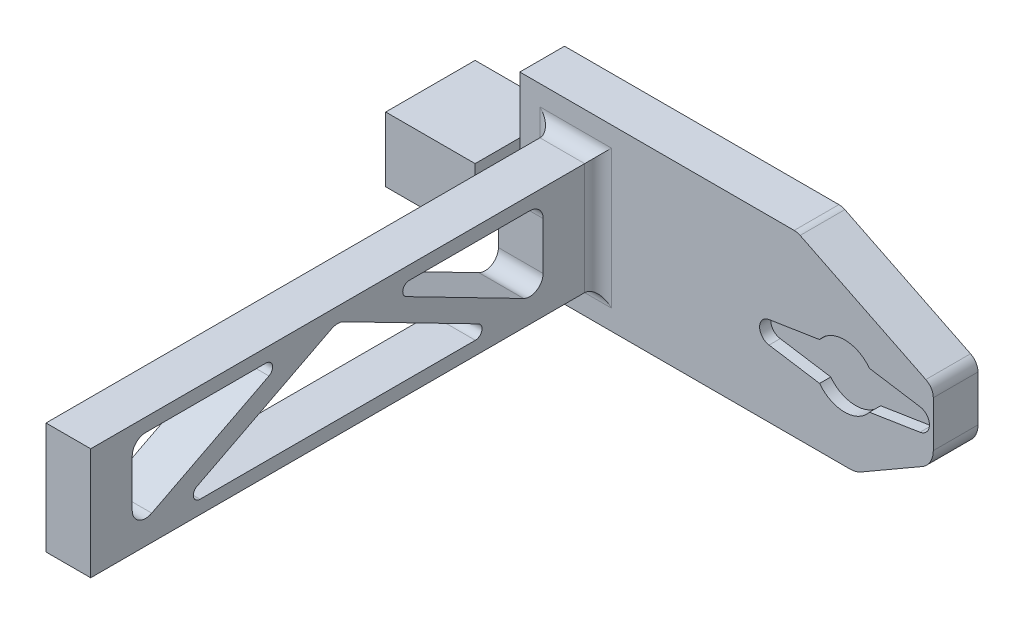
SolidWorks part; units mm, degrees
material "PLA"
ref_plane "Front Plane" through (0, 0, 0) normal (0, 0, 1) x (1, 0, 0)
ref_plane "Top Plane" through (0, 0, 0) normal (0, 1, 0) x (1, 0, 0)
ref_plane "Right Plane" through (0, 0, 0) normal (1, 0, 0) x (0, 0, -1)
sketch "Sketch3" plane through (0, 0, 0) normal (0, 0, 1) x (1, 0, 0)
  line L1 (-22.6388, -7.4411) -> (19.8612, -7.4411)
  line L2 (-22.6388, -7.4411) -> (-22.6388, 7.5589)
  line L3 (-22.6388, 7.5589) -> (19.8612, 7.5589)
  line L4 (19.8612, -7.4411) -> (19.8612, 7.5589)
  dimension "D1" = 15
  dimension "D2" = 42.5
extrude "Boss-Extrude1" add sketch "Sketch3" against normal blind 10
sketch "Sketch2" plane through (0, 0, 0) normal (0, 0, 1) x (1, 0, 0)
  line L0 (-16.8881, 2.4697) -> (-3.9686, 4.5)
  line L1 (-16.8881, -2.4697) -> (-3.9686, -4.5)
  line L2 (3.9686, 4.5) -> (16.8881, 2.4697)
  line L3 (16.8881, -2.4697) -> (3.9686, -4.5)
  line L4 (-16.9657, 2.9636) -> (-4.187, 4.9718)
  line L5 (4.187, 4.9718) -> (16.9657, 2.9636)
  line L6 (16.9657, -2.9636) -> (4.187, -4.9718)
  line L7 (-16.9657, -2.9636) -> (-4.187, -4.9718)
  arc A0 (-16.8881, 2.4697) -> (-16.8881, -2.4697) centre (-16.5, 0) ccw
  arc A1 (-3.9686, 4.5) -> (3.9686, 4.5) centre (0, 0) cw
  arc A2 (-3.9686, -4.5) -> (3.9686, -4.5) centre (0, 0) ccw
  arc A3 (16.8881, -2.4697) -> (16.8881, 2.4697) centre (16.5, 0) ccw
  arc A4 (-4.187, 4.9718) -> (4.187, 4.9718) centre (0, 0) cw
  arc A5 (16.9657, -2.9636) -> (16.9657, 2.9636) centre (16.5, 0) ccw
  arc A6 (-4.187, -4.9718) -> (4.187, -4.9718) centre (0, 0) ccw
  arc A7 (-16.9657, 2.9636) -> (-16.9657, -2.9636) centre (-16.5, 0) ccw
  circle A8 centre (0, 0) radius 7.0126
  dimension "D1" = 0.5
extrude "Cut-Extrude1" cut sketch "Sketch2" against normal blind 2.5 contours L3 A2 L1 A0 L0 A1 L2 A3 | A8
sketch "Sketch11" plane through (0, -7.4411, 0) normal (0, -1, 0) x (1, 0, 0)
  line L0 (8.25, 0) -> (-8.25, 0) construction
  line L1 (19.8612, -10) -> (-22.6388, -10)
  line L2 (19.8612, -10) -> (19.8612, 0)
  line L3 (19.8612, 0) -> (-22.6388, 0)
  line L4 (-22.6388, -10) -> (-22.6388, 0)
  line L5 (-22.6388, -10) -> (-22.6388, 0) construction
extrude "Boss-Extrude5" add sketch "Sketch11" along normal blind 10
sketch "Sketch14" plane through (0, 7.5589, 0) normal (0, 1, 0) x (1, 0, 0)
  line L0 (-8.25, 0) -> (8.25, 0) construction
  line L1 (19.8612, 10) -> (-22.6388, 10)
  line L2 (19.8612, 10) -> (19.8612, 0)
  line L3 (19.8612, 0) -> (-22.6388, 0)
  line L4 (-22.6388, 10) -> (-22.6388, 0)
  line L5 (-22.6388, 10) -> (-22.6388, 0) construction
extrude "Boss-Extrude7" add sketch "Sketch14" along normal blind 15
sketch "Sketch20" plane through (-22.6388, 0, 0) normal (-1, 0, 0) x (0, 0, 1)
  line L0 (0, -8.25) -> (0, 8.25) construction
  line L1 (-10, 22.5589) -> (0, 22.5589)
  line L2 (-10, 22.5589) -> (-10, -17.4411)
  line L3 (-10, -17.4411) -> (0, -17.4411)
  line L4 (0, 22.5589) -> (0, -17.4411)
  line L5 (0, -17.4411) -> (-10, -17.4411) construction
extrude "Boss-Extrude10" add sketch "Sketch20" along normal blind 50
sketch "Sketch21" plane through (0, 0, 0) normal (0, 0, 1) x (1, 0, 0)
  line L1 (-65.1388, 15.0589) -> (-55.1388, 15.0589)
  line L2 (-65.1388, 15.0589) -> (-65.1388, -9.9411)
  line L3 (-65.1388, -9.9411) -> (-55.1388, -9.9411)
  line L4 (-55.1388, 15.0589) -> (-55.1388, -9.9411)
  line L5 (-72.6388, 22.5589) -> (19.8612, 22.5589) construction
  line L6 (-72.6388, -17.4411) -> (-72.6388, 22.5589) construction
  dimension "D1" = 7.5
  dimension "D2" = 25
  dimension "D3" = 7.5
  dimension "D4" = 10
extrude "Boss-Extrude11" add sketch "Sketch21" along normal blind 113.5
fillet "Fillet1" radius 3 4 edges at (-60.1388, 15.0589, 0) (-65.1388, 2.5589, 0) (-55.1388, 2.5589, 0) (-60.1388, -9.9411, 0)
chamfer "Chamfer1" distance 15 angle 63.75 1 edges at (19.8612, 22.5589, -5)
fillet "Fillet2" radius 3 2 edges at (-10.5558, 22.5589, -5) (19.8612, 7.5589, -5)
chamfer "Chamfer2" distance 10 angle 60 1 edges at (19.8612, -17.4411, -5)
fillet "Fillet3" radius 5 2 edges at (2.5406, -17.4411, -5) (19.8612, -7.4411, -5)
sketch "Sketch24" plane through (-65.1388, 0, 0) normal (-1, 0, 0) x (0, 0, 1)
  line L0 (58.25, 15.0589) -> (58.25, -9.9411) construction
  line L1 (113.5, 15.0589) -> (3, 15.0589) construction
  line L2 (113.5, -9.9411) -> (3, -9.9411) construction
  line L3 (58.25, -6.9411) -> (95.25, -6.9411)
  line L4 (58.25, -6.9411) -> (21.25, -6.9411)
  line L5 (21.25, -6.9411) -> (58.25, 12.0589)
  line L6 (58.25, 12.0589) -> (95.25, -6.9411)
  line L7 (48.399, 12.0589) -> (12.29, -6.4835)
  line L8 (48.399, 12.0589) -> (12.29, 12.0589)
  line L9 (12.29, 12.0589) -> (12.29, -6.4835)
  line L10 (68.101, 12.0589) -> (104.21, 12.0589)
  line L11 (68.101, 12.0589) -> (104.21, -6.4835)
  line L12 (104.21, 12.0589) -> (104.21, -6.4835)
  dimension "D1" = 37
  dimension "D2" = 37
  dimension "D3" = 3
  dimension "D4" = 3
  dimension "D5" = 3
  dimension "D6" = 4.5
  dimension "D7" = 18.5424
extrude "Cut-Extrude2" cut sketch "Sketch24" against normal through all
fillet "Fillet4" radius 3 5 edges at (-60.1388, -6.4835, 12.29) (-60.1388, 12.0589, 12.29) (-60.1388, -6.4835, 104.21) (-60.1388, 12.0589, 104.21) (-60.1388, 12.0589, 58.25)
fillet "Fillet5" radius 1.5 4 edges at (-60.1388, 12.0589, 68.101) (-60.1388, -6.9411, 95.25) (-60.1388, -6.9411, 21.25) (-60.1388, 12.0589, 48.399)
sketch "Sketch25" plane through (-72.6388, 0, 0) normal (-1, 0, 0) x (0, 0, 1)
  line L0 (0, 22.5589) -> (-10, 22.5589) construction
  line L1 (-10, -17.4411) -> (0, -17.4411) construction
  line L2 (-5, 22.5589) -> (-5, -17.4411) construction
  line L3 (0, -22) -> (0, 22) construction
  line L4 (-10, -4.6911) -> (0, -4.6911)
  line L5 (-10, -4.6911) -> (-10, 9.8089)
  line L6 (-10, 9.8089) -> (0, 9.8089)
  line L7 (0, -4.6911) -> (0, 9.8089)
  line L8 (-10, -4.6911) -> (0, 9.8089) construction
  line L9 (-10, 9.8089) -> (0, -4.6911) construction
  point P6 (-5, 2.5589)
  dimension "D1" = 14.5
extrude "Boss-Extrude12" add sketch "Sketch25" along normal blind 20
sketch "Sketch26" plane through (0, 0, 0) normal (0, 0, 1) x (1, 0, 0)
  line L1 (-72.6388, 9.8089) -> (-92.6388, 9.8089)
  line L2 (-72.6388, 9.8089) -> (-72.6388, -4.6911)
  line L3 (-72.6388, -4.6911) -> (-92.6388, -4.6911)
  line L4 (-92.6388, 9.8089) -> (-92.6388, -4.6911)
  line L5 (-72.6388, 9.8089) -> (-92.6388, -4.6911) construction
  line L6 (-72.6388, -4.6911) -> (-92.6388, 9.8089) construction
  point P4 (-82.6388, 2.5589)
extrude "Boss-Extrude13" add sketch "Sketch26" along normal blind 10
